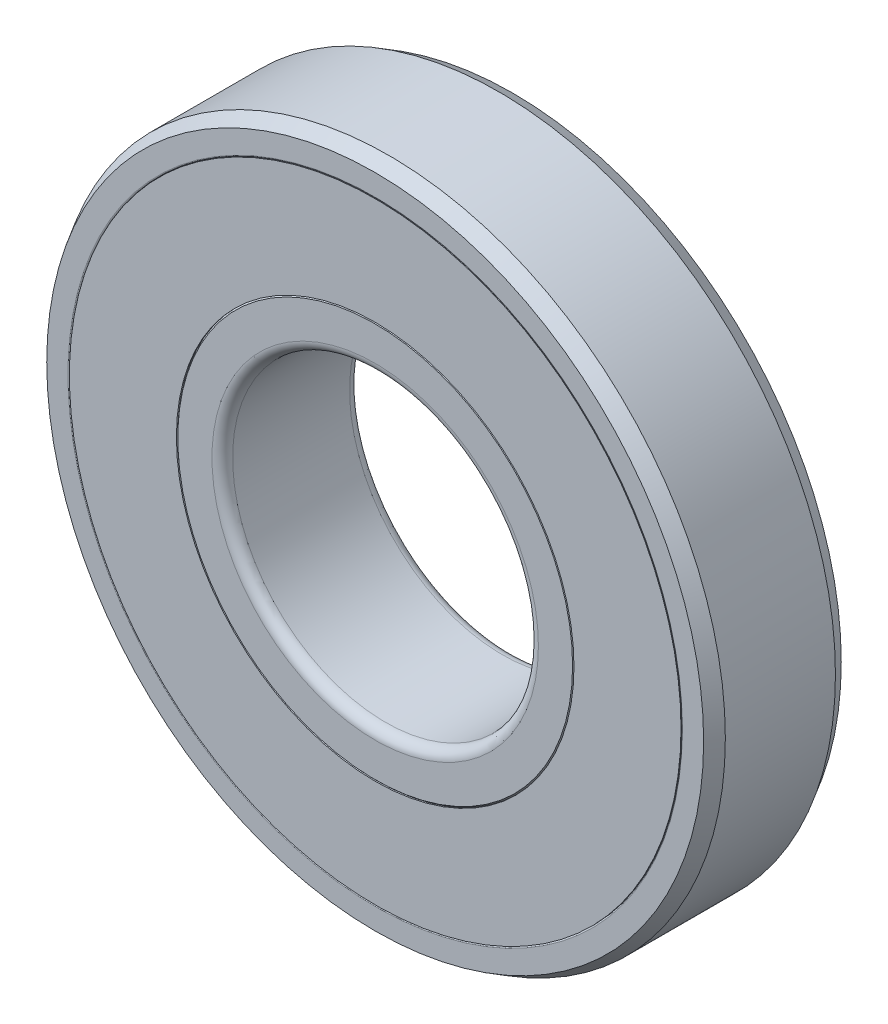
SolidWorks part; units mm, degrees
ref_plane "Front Plane" through (0, 0, 0) normal (0, 0, 1) x (1, 0, 0)
ref_plane "Top Plane" through (0, 0, 0) normal (0, 1, 0) x (1, 0, 0)
ref_plane "Right Plane" through (0, 0, 0) normal (1, 0, 0) x (0, 0, -1)
sketch "Sketch1" plane through (0, 0, 0) normal (0, 0, 1) x (1, 0, 0)
  line L0 (0, 12.7) -> (0, 17.4625) construction
  line L1 (0, 7.9375) -> (0, 12.7) construction
  line L2 (0, 17.4625) -> (0, 15.875) construction
  line L3 (0, 15.875) -> (0, 14.2875) construction
  line L4 (0, 14.2875) -> (0, 12.7) construction
  circle A0 centre (0, 0) radius 7.9375
  circle A1 centre (0, 0) radius 17.4625
  circle A2 centre (0, 0) radius 15.875 construction
  circle A4 centre (0, 0) radius 10.3187 construction
  point P6 (0, 10.3187)
  dimension "OD" = 34.925
  dimension "ID" = 15.875
sketch "Sketch2" plane through (0, 0, 0) normal (1, 0, 0) x (0, 0, -1)
  line L0 (-3.5719, 17.4625) -> (3.5719, 17.4625) construction
  line L1 (3.5719, 17.4625) -> (3.5719, -17.4625) construction
  line L2 (3.5719, 0) -> (-3.5719, 0) construction
  line L3 (-3.5719, 7.9375) -> (-3.5719, -7.9375) construction
  point P2 (0, 17.4625)
  dimension "Width" = 7.1437
  dimension "For Shaft Diameter" = 15.875
  dimension "For Housing ID" = 34.925
sketch "Sketch3" plane through (0, 0, 0) normal (1, 0, 0) x (0, 0, -1)
  line L0 (-2.8575, -17.4625) -> (2.8575, -17.4625)
  line L3 (-3.5719, -15.9464) -> (-3.5719, -17.0501)
  line L4 (0, -10.3187) -> (0, -15.875) construction
  line L5 (-2.8575, -17.4625) -> (-3.5719, -17.0501)
  line L6 (-3.0361, -7.9375) -> (3.0361, -7.9375)
  line L7 (-3.2147, -13.0969) -> (-3.5719, -13.0969) construction
  line L8 (-3.5004, -10.3187) -> (-1.6175, -10.3188)
  line L9 (-3.5719, -10.3188) -> (0, -10.3187) construction
  line L11 (-3.5719, -15.875) -> (-3.5719, -10.3188) construction
  line L12 (-3.5719, -10.2473) -> (-3.5719, -8.4733)
  line L14 (-3.5719, 0) -> (3.5719, 0) construction
  line L15 (-3.5004, -15.875) -> (-1.6175, -15.875)
  line L17 (0, 0) -> (0, -17.4625) construction
  line L18 (-3.5719, 17.4625) -> (3.5719, 17.4625) construction
  line L19 (2.8575, -17.4625) -> (3.5719, -17.0501)
  line L20 (0, -15.875) -> (-3.5719, -15.875) construction
  line L30 (-3.5719, -10.2473) -> (-3.5004, -10.3187)
  line L31 (3.5004, -10.3187) -> (1.6175, -10.3188)
  line L32 (3.5719, -10.2473) -> (3.5004, -10.3187)
  line L33 (3.5719, -10.2473) -> (3.5719, -8.4733)
  line L34 (3.5004, -15.875) -> (1.6175, -15.875)
  line L35 (3.5719, -15.9464) -> (3.5719, -17.0501)
  line L36 (0, 17.4625) -> (0, -17.4625) construction
  arc A0 (0, -9.8822) -> (0, -16.3116) centre (0, -13.0969) ccw construction
  arc A1 (-1.6175, -10.3188) -> (1.6175, -10.3188) centre (0, -13.0969) cw
  arc A2 (-1.6175, -15.875) -> (1.6175, -15.875) centre (0, -13.0969) ccw
  arc A4 (-3.5004, -15.875) -> (-3.5719, -15.9464) centre (-3.5004, -15.9464) ccw
  arc A5 (-3.0361, -7.9375) -> (-3.5719, -8.4733) centre (-3.0361, -8.4733) ccw
  arc A6 (3.0361, -7.9375) -> (3.5719, -8.4733) centre (3.0361, -8.4733) cw
  arc A7 (3.5004, -15.875) -> (3.5719, -15.9464) centre (3.5004, -15.9464) cw
  point P28 (0, -13.0969)
  point P46 (-3.5719, -7.9375)
  point P54 (0, -7.9375)
  dimension "D4" = 0.0714
  dimension "D7" = 0.5358
  dimension "D1" = 0.3572
  dimension "D5" = 45
  dimension "D6" = 0.0714
  dimension "D2" = 30
  dimension "D3" = 0.7144
revolve "Revolve1" add sketch "Sketch3" angle 360 about L14
sketch "Sketch4" plane through (0, 0, 0) normal (1, 0, 0) x (0, 0, -1)
  line L0 (-3.5004, -15.875) -> (-1.6175, -15.875) construction
  line L1 (-3.5719, -10.3188) -> (-3.2147, -10.3188)
  line L2 (-3.5719, -10.3188) -> (-3.5719, -15.875)
  line L3 (-3.5719, -15.875) -> (-3.2147, -15.875)
  line L4 (-3.2147, -10.3188) -> (-3.2147, -15.875)
  line L5 (-3.5719, -10.2473) -> (-3.5719, -8.4733) construction
revolve "Revolve2" add sketch "Sketch4" angle 360 about L14
sketch "Sketch5" plane through (0, 0, 0) normal (1, 0, 0) x (0, 0, -1)
  line L2 (0, -9.8822) -> (0, -16.3116)
  arc A2 (0, -16.3116) -> (0, -9.8822) centre (0, -13.0969) cw
revolve "Revolve3" add sketch "Sketch5" angle 360 about L17
pattern_circular "CirPattern1" count 7 over 360 about axis through (0, 0, 0) along (0, 0, 1) of bodies 138
equation "\"D1@Sketch3\"=\"Width@Sketch2\"*.05"
equation "\"D4@Sketch3\"=\"Width@Sketch2\"*.01"
equation "\"D6@Sketch3\"=\"Width@Sketch2\"*.01"
equation "\"D7@Sketch3\"=\"Width@Sketch2\"*.075"
equation "\"D3@Sketch3\"=\"Width@Sketch2\"*.1"
